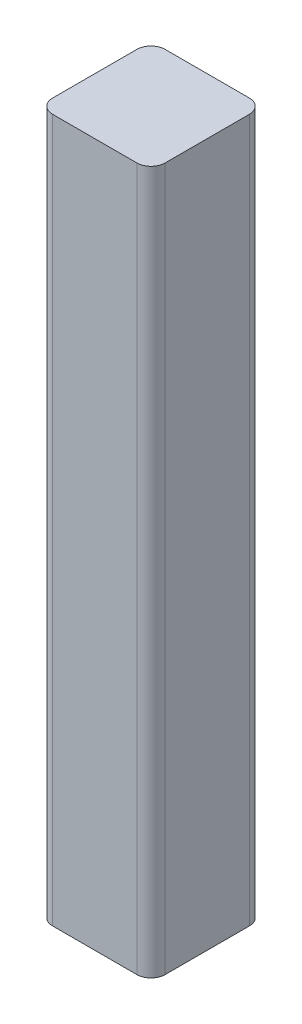
SolidWorks part; units mm, degrees
ref_plane "Front Plane" through (0, 0, 0) normal (0, 0, 1) x (1, 0, 0)
ref_plane "Top Plane" through (0, 0, 0) normal (0, 1, 0) x (1, 0, 0)
ref_plane "Right Plane" through (0, 0, 0) normal (1, 0, 0) x (0, 0, -1)
sketch "Sketch1" plane through (0, 0, 0) normal (0, 1, 0) x (1, 0, 0)
  line L1 (-20, -20) -> (20, -20)
  line L2 (-20, -20) -> (-20, 20)
  line L3 (-20, 20) -> (20, 20)
  line L4 (20, -20) -> (20, 20)
  line L5 (-20, -20) -> (20, 20) construction
  line L6 (-20, 20) -> (20, -20) construction
  point P0 (0, 0)
  dimension "D1" = 40
  dimension "D2" = 40
extrude "Boss-Extrude1" add sketch "Sketch1" along normal blind 250
fillet "Fillet1" radius 5 4 edges at (-20, 125, 20) (-20, 125, -20) (20, 125, -20) (20, 125, 20)
